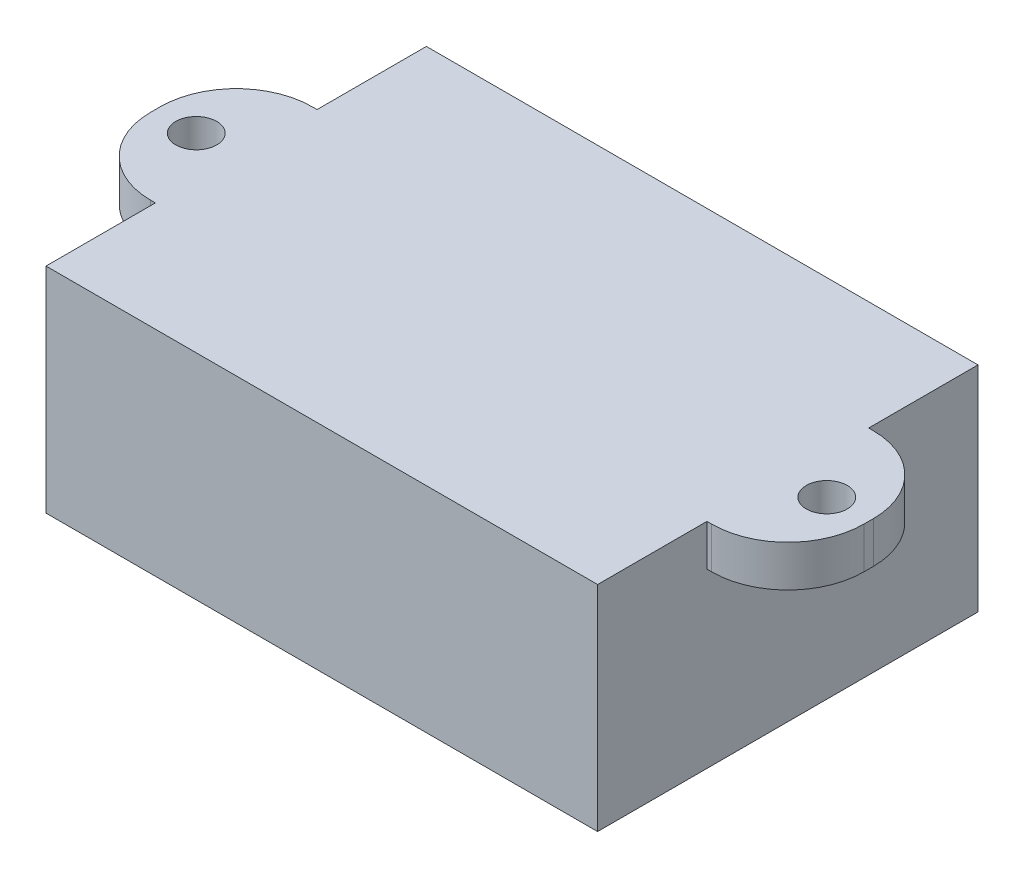
SolidWorks part; units mm, degrees
ref_plane "Front Plane" through (0, 0, 0) normal (0, 0, 1) x (1, 0, 0)
ref_plane "Top Plane" through (0, 0, 0) normal (0, 1, 0) x (1, 0, 0)
ref_plane "Right Plane" through (0, 0, 0) normal (1, 0, 0) x (0, 0, -1)
sketch "Sketch1" plane through (0, 0, 0) normal (0, 1, 0) x (1, 0, 0)
  line L1 (0, 0) -> (58, 0)
  line L2 (0, 0) -> (0, -40)
  line L3 (0, -40) -> (58, -40)
  line L4 (58, 0) -> (58, -40)
  dimension "D1" = 58
  dimension "D2" = 40
extrude "Boss-Extrude1" add sketch "Sketch1" along normal blind 22.5
sketch "Sketch2" plane through (0, 22.5, 0) normal (0, 1, 0) x (1, 0, 0)
  line L0 (58, -40) -> (58, 0) construction
  line L1 (58, -11.5) -> (66.5, -11.5)
  line L2 (58, -11.5) -> (58, -28.5)
  line L3 (58, -28.5) -> (66.5, -28.5)
  line L4 (66.5, -11.5) -> (66.5, -28.5)
  line L5 (0, 0) -> (0, -40) construction
  line L6 (0, -11.5) -> (-8.5, -11.5)
  line L7 (0, -11.5) -> (0, -28.5)
  line L8 (0, -28.5) -> (-8.5, -28.5)
  line L9 (-8.5, -11.5) -> (-8.5, -28.5)
  circle A0 centre (-4.2, -20) radius 2.15
  circle A1 centre (62.1, -20) radius 2.15
  point P12 (0, -20)
  point P13 (0, -20)
  point P14 (66.5, -20)
  point P15 (58, -20)
  point P18 (0, 0)
  dimension "D7" = 4.3
  dimension "D8" = 0
  dimension "D1" = 17
  dimension "D2" = 17
  dimension "D3" = 0
  dimension "D4" = 0
  dimension "D5" = 8.5
  dimension "D6" = 8.5
  dimension "D10" = 4.2
  dimension "D9" = 2
extrude "Boss-Extrude2" add sketch "Sketch2" against normal blind 4.35
fillet "Fillet1" radius 8 4 edges at (-8.5, 20.325, 28.5) (-8.5, 20.325, 11.5) (66.5, 20.325, 28.5) (66.5, 20.325, 11.5)
